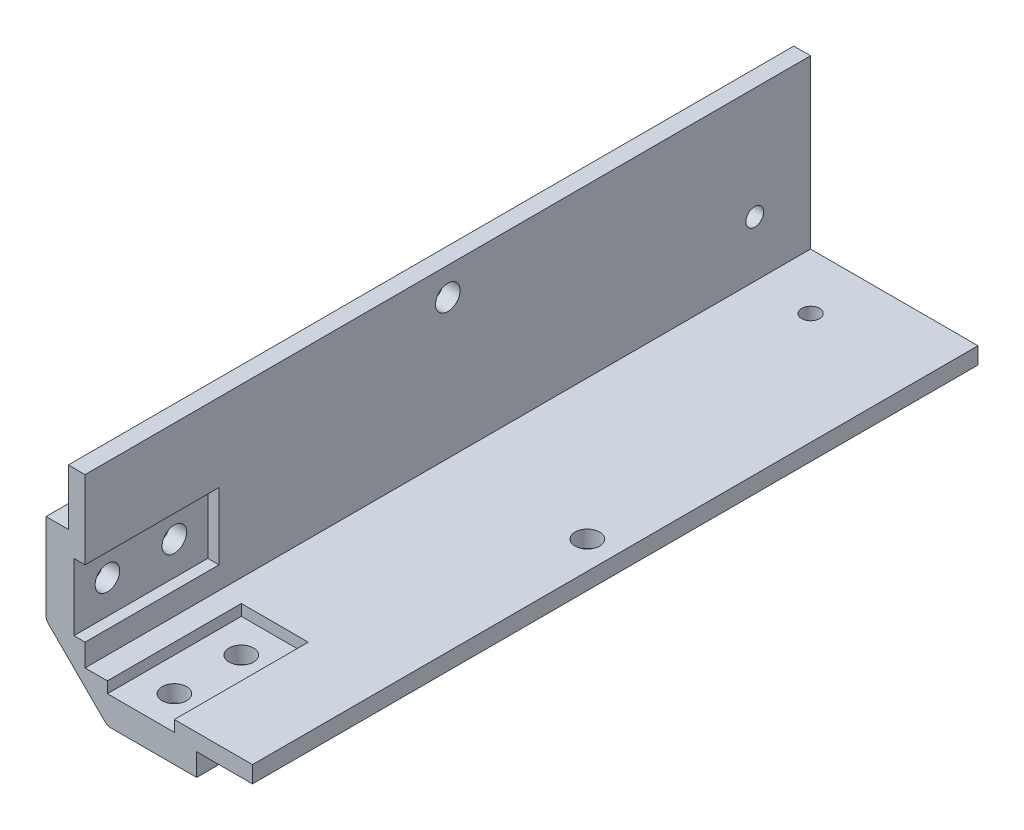
SolidWorks part; units mm, degrees
ref_plane "Front Plane" through (0, 0, 0) normal (0, 0, 1) x (1, 0, 0)
ref_plane "Top Plane" through (0, 0, 0) normal (0, 1, 0) x (1, 0, 0)
ref_plane "Right Plane" through (0, 0, 0) normal (1, 0, 0) x (0, 0, -1)
ref_plane "Plane1" through (0, 0, 280) normal (0, 0, 1) x (1, 0, 0)
sketch "Sketch1" plane through (0, 0, 280) normal (0, 0, 1) x (1, 0, 0)
  line L0 (-7, 4) -> (4, -7)
  line L1 (4, -7) -> (7, -7)
  line L2 (7, -7) -> (7, -3)
  line L3 (7, -3) -> (20, -3)
  line L4 (20, -3) -> (20, 0)
  line L5 (20, 0) -> (0, 0)
  line L6 (0, 0) -> (0, 20)
  line L7 (0, 20) -> (-3, 20)
  line L8 (-3, 20) -> (-3, 7)
  line L9 (-3, 7) -> (-7, 7)
  line L10 (-7, 7) -> (-7, 4)
extrude "Boss-Extrude1" add sketch "Sketch1" against normal blind 130
fillet "Fillet1" radius 1.5 2 edges at (-7, 4, 215) (4, -7, 215)
sketch "Sketch4" plane through (0, -3, 0) normal (0, -1, 0) x (1, 0, 0)
  line L4 (20, 280) -> (7, 280)
  line L5 (7, 280) -> (7, 150)
  line L6 (7, 150) -> (20, 150)
  line L7 (20, 150) -> (20, 280)
  line L8 (20, 280) -> (7, 280)
  line L9 (7, 280) -> (7, 150)
  line L10 (7, 150) -> (20, 150)
  line L11 (20, 150) -> (20, 280)
  dimension "D1" = 0
sketch "Sketch2" plane through (20, 0, 0) normal (1, 0, 0) x (0, 0, -1)
  line L4 (-280, 0) -> (-280, -3)
  line L5 (-280, -3) -> (-150, -3)
  line L6 (-150, -3) -> (-150, 0)
  line L7 (-150, 0) -> (-280, 0)
  line L8 (-280, 0) -> (-280, -3)
  line L9 (-280, -3) -> (-150, -3)
  line L10 (-150, -3) -> (-150, 0)
  line L11 (-150, 0) -> (-280, 0)
  dimension "D1" = 0
extrude "Boss-Extrude2" add sketch "Sketch2" along normal blind 10
extrude "Boss-Extrude3" add sketch "Sketch4" along normal up to surface (4 mm away) up to face at (5.8107, -7, 215)
sketch "Sketch5" plane through (-3, 0, 0) normal (-1, 0, 0) x (0, 0, 1)
  line L4 (280, 7) -> (280, 20)
  line L5 (280, 20) -> (150, 20)
  line L6 (150, 20) -> (150, 7)
  line L7 (150, 7) -> (280, 7)
  line L8 (280, 7) -> (280, 20)
  line L9 (280, 20) -> (150, 20)
  line L10 (150, 20) -> (150, 7)
  line L11 (150, 7) -> (280, 7)
  dimension "D1" = 0
sketch "Sketch6" plane through (0, 20, 0) normal (0, 1, 0) x (1, 0, 0)
  line L4 (-3, -280) -> (0, -280)
  line L5 (0, -280) -> (0, -150)
  line L6 (0, -150) -> (-3, -150)
  line L7 (-3, -150) -> (-3, -280)
  line L8 (-3, -280) -> (0, -280)
  line L9 (0, -280) -> (0, -150)
  line L10 (0, -150) -> (-3, -150)
  line L11 (-3, -150) -> (-3, -280)
  dimension "D1" = 0
extrude "Boss-Extrude4" add sketch "Sketch6" along normal blind 10
extrude "Boss-Extrude5" add sketch "Sketch5" along normal up to surface (4 mm away) up to face at (-7, 5.8107, 215)
sketch "Sketch7" plane through (0, 0, 0) normal (1, 0, 0) x (0, 0, -1)
  line L0 (-280, 55) -> (-280, -55) construction
  line L1 (-280, 0) -> (-150, 0) construction
  line L2 (-280, 0) -> (-280, 20) construction
  line L3 (-280, 20) -> (-150, 20) construction
  line L4 (-150, 0) -> (-150, 20) construction
  line L5 (-150, 0) -> (-280, 0) construction
  line L7 (-150, 0) -> (-150, 30) construction
  line L8 (-280, 10) -> (-150, 10) construction
  point P13 (-270, 10)
  point P14 (-160, 10)
  dimension "D1" = 20
  dimension "D2" = 10
  dimension "D3" = 10
sketch "Sketch8" plane through (-7, 0, 0) normal (-1, 0, 0) x (0, 0, 1)
  point P0 (160, 10)
  point P2 (270, 10)
hole_wizard "CSK for M3 SFHCS1" positions "Sketch8" profile "Sketch9" countersink size "M3" standard "ANSI Metric"
sketch "Sketch9" plane through (-7, 10, 160) normal (0, 1, 0) x (0, 0, 1)
  line L0 (0, 0) -> (0, 37)
  line L1 (0, 37) -> (1.6, 37)
  line L2 (1.6, 37) -> (1.6, 1.76)
  line L3 (1.6, 1.76) -> (3.36, 0)
  line L5 (3.36, 0) -> (0, 0)
  line L6 (-1.6, 1.76) -> (-3.36, 0) construction
  line L11 (0, -6.35) -> (0, 107.95) construction
  dimension "Thru Hole Dia." = 3.2
  dimension "Thru Hole Depth" = 37
  dimension "Near C'Sink Dia." = 6.72
  dimension "Near C'Sink Angle" = 90
sketch "Sketch10" plane through (0, 0, 0) normal (0, 1, 0) x (1, 0, 0)
  line L0 (10, -150) -> (10, -280) construction
  line L1 (30, -150) -> (0, -150) construction
  line L2 (-55, -280) -> (55, -280) construction
  line L3 (0, -280) -> (0, -150) construction
  point P8 (10, -160)
  point P9 (10, -270)
  dimension "D1" = 10
  dimension "D2" = 10
  dimension "D3" = 10
sketch "Sketch11" plane through (0, -7, 0) normal (0, -1, 0) x (1, 0, 0)
  point P0 (10, 160)
  point P2 (10, 270)
hole_wizard "CSK for M3 SFHCS2" positions "Sketch11" profile "Sketch12" countersink size "M3" standard "ANSI Metric"
sketch "Sketch12" plane through (10, -7, 160) normal (1, 0, 0) x (0, 0, -1)
  line L0 (0, 0) -> (0, 37)
  line L1 (0, 37) -> (1.6, 37)
  line L2 (1.6, 37) -> (1.6, 1.76)
  line L3 (1.6, 1.76) -> (3.36, 0)
  line L5 (3.36, 0) -> (0, 0)
  line L6 (-1.6, 1.76) -> (-3.36, 0) construction
  line L11 (0, -6.35) -> (0, 107.95) construction
  dimension "Thru Hole Dia." = 3.2
  dimension "Thru Hole Depth" = 37
  dimension "Near C'Sink Dia." = 6.72
  dimension "Near C'Sink Angle" = 90
sketch "Sketch13" plane through (0, 0, 0) normal (0, 1, 0) x (1, 0, 0)
  line L1 (4, -280) -> (16, -280)
  line L2 (4, -280) -> (4, -256)
  line L3 (4, -256) -> (16, -256)
  line L4 (16, -280) -> (16, -256)
  line L5 (-55, -280) -> (55, -280) construction
  line L6 (0, -280) -> (0, -150) construction
  line L7 (10, -150) -> (10, -280) construction
  point P8 (0, 0)
  dimension "D1" = 4
  dimension "D2" = 6
  dimension "D3" = 24
extrude "Cut-Extrude1" cut sketch "Sketch13" against normal blind 2
sketch "Sketch14" plane through (0, -2, 0) normal (0, 1, 0) x (1, 0, 0)
  line L0 (10, -256) -> (10, -280) construction
  line L1 (16, -256) -> (4, -256) construction
  point P5 (10, -274)
  point P6 (10, -262)
  dimension "D1" = 12
  dimension "D2" = 6
hole_wizard "Ø4.4 (4.4) Diameter Hole1" positions "Sketch14" profile "Sketch15" hole size "Ø4.4" standard "ANSI Metric"
sketch "Sketch15" plane through (10, -2, 262) normal (1, 0, 0) x (0, 0, 1)
  line L0 (0, 0) -> (0, 3)
  line L1 (0, 3) -> (2.2, 3)
  line L2 (2.2, 3) -> (2.2, 0)
  line L5 (2.2, 0) -> (0, 0)
  line L10 (0, 3) -> (-2.2, 3) construction
  line L11 (0, -6.35) -> (0, 107.95) construction
  dimension "Hole Dia." = 4.4
  dimension "Hole Depth" = 3
  dimension "Drill Angle" = 180
sketch "Sketch16" plane through (0, 0, 0) normal (1, 0, 0) x (0, 0, -1)
  line L0 (-280, 0) -> (-280, 20) construction
  line L1 (-280, 16) -> (-256, 16)
  line L2 (-280, 16) -> (-280, 4)
  line L3 (-280, 4) -> (-256, 4)
  line L4 (-256, 16) -> (-256, 4)
  line L5 (-280, 0) -> (-150, 0) construction
  line L7 (-280, 10) -> (-150, 10) construction
  dimension "D1" = 4
  dimension "D2" = 6
  dimension "D3" = 24
extrude "Cut-Extrude2" cut sketch "Sketch16" against normal blind 2 contours L1 L4 L3 L2
sketch "Sketch17" plane through (-2, 0, 0) normal (1, 0, 0) x (0, 0, -1)
  line L0 (-280, 10) -> (-255.8027, 10) construction
  line L1 (-280, 0) -> (-280, 20) construction
  line L2 (-280, 10) -> (-150, 10) construction
  line L3 (-280, 16) -> (-280, 4) construction
  point P6 (-274, 10)
  point P7 (-262, 10)
  dimension "D1" = 12
  dimension "D2" = 6
hole_wizard "Ø4.4 (4.4) Diameter Hole2" positions "Sketch17" profile "Sketch18" hole size "Ø4.4" standard "ANSI Metric"
sketch "Sketch18" plane through (-2, 10, 262) normal (0, 1, 0) x (0, 0, -1)
  line L0 (0, 0) -> (0, 3)
  line L1 (0, 3) -> (2.2, 3)
  line L2 (2.2, 3) -> (2.2, 0)
  line L5 (2.2, 0) -> (0, 0)
  line L10 (0, 3) -> (-2.2, 3) construction
  line L11 (0, -6.35) -> (0, 107.95) construction
  dimension "Hole Dia." = 4.4
  dimension "Hole Depth" = 3
  dimension "Drill Angle" = 180
sketch "Sketch19" plane through (-3, 0, 0) normal (-1, 0, 0) x (0, 0, 1)
  line L0 (150, 25) -> (280, 25) construction
  line L1 (150, 30) -> (150, 20) construction
  line L2 (280, -55) -> (280, 55) construction
  point P6 (215, 25)
  point P8 (0, 0)
hole_wizard "Ø4.4 (4.4) Diameter Hole3" positions "Sketch19" profile "Sketch20" hole size "Ø4.4" standard "ANSI Metric"
sketch "Sketch20" plane through (-3, 25, 215) normal (0, 1, 0) x (0, 0, 1)
  line L0 (0, 0) -> (0, 3)
  line L1 (0, 3) -> (2.2, 3)
  line L2 (2.2, 3) -> (2.2, 0)
  line L5 (2.2, 0) -> (0, 0)
  line L10 (0, 3) -> (-2.2, 3) construction
  line L11 (0, -6.35) -> (0, 107.95) construction
  dimension "Hole Dia." = 4.4
  dimension "Hole Depth" = 3
  dimension "Drill Angle" = 180
sketch "Sketch21" plane through (0, -3, 0) normal (0, -1, 0) x (1, 0, 0)
  line L0 (25, 150) -> (25, 280) construction
  line L1 (20, 150) -> (30, 150) construction
  line L2 (55, 280) -> (-55, 280) construction
  point P6 (25, 215)
hole_wizard "Ø4.4 (4.4) Diameter Hole4" positions "Sketch21" profile "Sketch22" hole size "Ø4.4" standard "ANSI Metric"
sketch "Sketch22" plane through (25, -3, 215) normal (1, 0, 0) x (0, 0, -1)
  line L0 (0, 0) -> (0, 3)
  line L1 (0, 3) -> (2.2, 3)
  line L2 (2.2, 3) -> (2.2, 0)
  line L5 (2.2, 0) -> (0, 0)
  line L10 (0, 3) -> (-2.2, 3) construction
  line L11 (0, -6.35) -> (0, 107.95) construction
  dimension "Hole Dia." = 4.4
  dimension "Hole Depth" = 3
  dimension "Drill Angle" = 180
